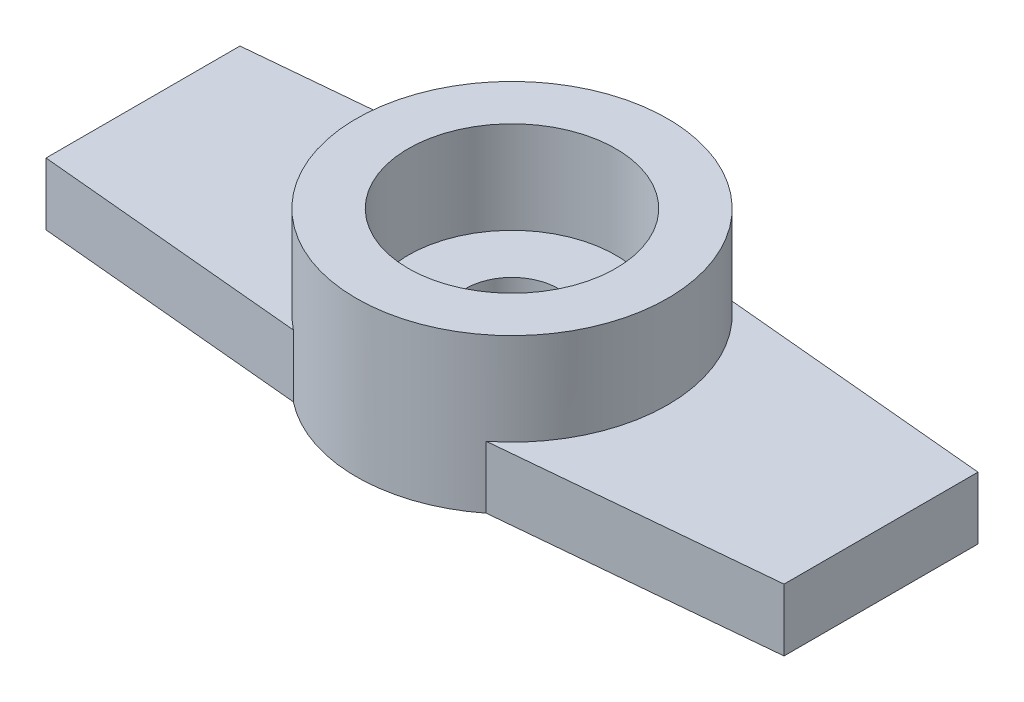
SolidWorks part; units mm, degrees
ref_plane "Piano frontale" through (0, 0, 0) normal (0, 0, 1) x (1, 0, 0)
ref_plane "Piano superiore" through (0, 0, 0) normal (0, 1, 0) x (1, 0, 0)
ref_plane "Piano destro" through (0, 0, 0) normal (1, 0, 0) x (0, 0, -1)
sketch "Schizzo1" plane through (0, 0, 0) normal (0, 1, 0) x (1, 0, 0)
  line L0 (-2.09, 2.65) -> (-14.5, 1.5)
  line L1 (-2.09, -2.65) -> (-14.5, -1.5)
  line L2 (-2.09, 2.65) -> (-2.09, -2.65)
  line L3 (8, -2.1023) -> (8, 2.1023)
  line L4 (2.09, 2.65) -> (2.09, -2.65)
  line L5 (2.09, -2.65) -> (14.5, -1.5)
  line L6 (2.09, 2.65) -> (14.5, 1.5)
  line L7 (-8, -2.1023) -> (-8, 2.1023)
  circle A0 centre (0, 0) radius 3.375
  arc A1 (-14.5, 1.5) -> (-14.5, -1.5) centre (-14.5, 0) ccw
  arc A2 (14.5, 1.5) -> (14.5, -1.5) centre (14.5, 0) cw
  point P8 (-2.09, 0)
  point P13 (-16, 0)
  point P14 (16, 0)
  point P18 (2.09, 0)
  dimension "D1" = 6.75
  dimension "D3" = 1.5
  dimension "D7" = 1.5
  dimension "D2" = 5.3
  dimension "D4" = 3
  dimension "D5" = 16
  dimension "D6" = 16
  dimension "D8" = 3
  dimension "D9" = 5.3
  dimension "D10" = 8
  dimension "D11" = 8
extrude "Estrusione-Estrusione1" add sketch "Schizzo1" along normal blind 1.35 contours A0 L5 L3 L6 | L4 A0 L2 | A0 L0 L7 L1 | L2 A0 | L4 A0
sketch "Schizzo2" plane through (0, 1.35, 0) normal (0, 1, 0) x (1, 0, 0)
  circle A0 centre (0, 0) radius 3.375
  dimension "D1" = 6.75
extrude "Estrusione-Estrusione2" add sketch "Schizzo2" along normal blind 2
sketch "Schizzo3" plane through (0, 3.35, 0) normal (0, 1, 0) x (1, 0, 0)
  circle A0 centre (0, 0) radius 2.25
  dimension "D1" = 4.5
extrude "Taglio-Estrusione1" cut sketch "Schizzo3" against normal blind 2
sketch "Schizzo4" plane through (0, 1.35, 0) normal (0, 1, 0) x (1, 0, 0)
  circle A0 centre (0, 0) radius 1
  dimension "D1" = 2
extrude "Taglio-Estrusione2" cut sketch "Schizzo4" against normal through all
